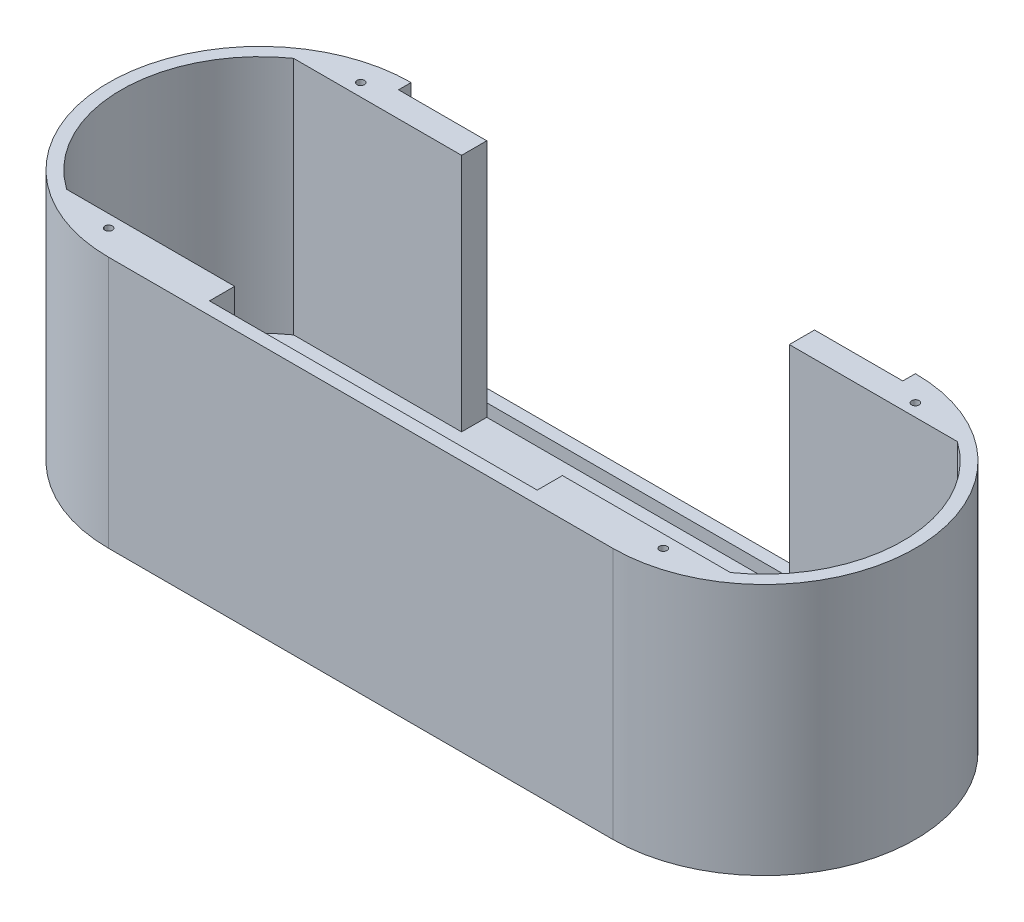
SolidWorks part; units mm, degrees
ref_plane "Front Plane" through (0, 0, 0) normal (0, 0, 1) x (1, 0, 0)
ref_plane "Top Plane" through (0, 0, 0) normal (0, 1, 0) x (1, 0, 0)
ref_plane "Right Plane" through (0, 0, 0) normal (1, 0, 0) x (0, 0, -1)
sketch "Sketch1" plane through (0, 0, 0) normal (0, 1, 0) x (1, 0, 0)
  line L0 (-10, 0) -> (10, 0) construction
  line L1 (-10, 6) -> (10, 6)
  line L2 (-10, -6) -> (10, -6)
  arc A0 (-10, 6) -> (-10, -6) centre (-10, 0) ccw
  arc A1 (10, -6) -> (10, 6) centre (10, 0) ccw
  point P3 (0, 0)
  point P8 (0, 0)
  dimension "D2" = 6
  dimension "D1" = 20
extrude "Boss-Extrude1" add sketch "Sketch1" along normal blind 10
sketch "Sketch2" plane through (0, 10, 0) normal (0, 1, 0) x (1, 0, 0)
  line L0 (-10, 0) -> (10, 0) construction
  line L1 (-10, 5.5) -> (10, 5.5)
  line L2 (-10, -5.5) -> (10, -5.5)
  arc A0 (-10, 5.5) -> (-10, -5.5) centre (-10, 0) ccw
  arc A1 (10, -5.5) -> (10, 5.5) centre (10, 0) ccw
  arc A2 (10, -6) -> (10, 6) centre (10, 0) ccw construction
  point P3 (0, 0)
  point P8 (0, 0)
  point P13 (16, 0)
  point P14 (0, 0)
  dimension "D1" = 5.5
extrude "Cut-Extrude1" cut sketch "Sketch2" against normal blind 9.5
sketch "Sketch3" plane through (0, 0, 0) normal (0, -1, 0) x (1, 0, 0)
  line L0 (-13, 3) -> (-7, -3) construction
  line L1 (-13, -3) -> (-7, 3) construction
  line L2 (0, 6) -> (0, -6) construction
  line L3 (-10, 6) -> (10, 6) construction
  line L4 (10, -6) -> (-10, -6) construction
  line L5 (13, -3) -> (7, 3) construction
  line L6 (13, 3) -> (7, -3) construction
  circle A0 centre (-13, 3) radius 0.15
  circle A1 centre (-7, 3) radius 0.15
  circle A2 centre (-13, -3) radius 0.15
  circle A3 centre (-7, -3) radius 0.15
  circle A4 centre (-12.5, 0) radius 0.5
  circle A5 centre (-12.0225, 1.4695) radius 0.5
  circle A6 centre (-10.7725, 2.3776) radius 0.5
  circle A7 centre (-9.2275, 2.3776) radius 0.5
  circle A8 centre (-7.9775, 1.4695) radius 0.5
  circle A9 centre (-7.5, 0) radius 0.5
  circle A10 centre (-7.9775, -1.4695) radius 0.5
  circle A11 centre (-9.2275, -2.3776) radius 0.5
  circle A12 centre (-10.7725, -2.3776) radius 0.5
  circle A13 centre (-12.0225, -1.4695) radius 0.5
  circle A14 centre (12.0225, -1.4695) radius 0.5
  circle A15 centre (10.7725, -2.3776) radius 0.5
  circle A16 centre (9.2275, -2.3776) radius 0.5
  circle A17 centre (7.9775, -1.4695) radius 0.5
  circle A18 centre (7.5, 0) radius 0.5
  circle A19 centre (7.9775, 1.4695) radius 0.5
  circle A20 centre (9.2275, 2.3776) radius 0.5
  circle A21 centre (10.7725, 2.3776) radius 0.5
  circle A22 centre (12.0225, 1.4695) radius 0.5
  circle A23 centre (12.5, 0) radius 0.5
  circle A24 centre (7, -3) radius 0.15
  circle A25 centre (13, -3) radius 0.15
  circle A26 centre (7, 3) radius 0.15
  circle A27 centre (13, 3) radius 0.15
  point P8 (-10, 0)
  point P33 (-10, 0)
  point P66 (10, 0)
  point P67 (-7.2566, 0)
  point P68 (-7.2332, 0)
  dimension "D1" = 0.3
  dimension "D5" = 1
  dimension "D2" = 6
  dimension "D3" = 6
  dimension "D6" = 2.5
  dimension "D4" = 10
extrude "Cut-Extrude2" cut sketch "Sketch3" against normal through all
sketch "Sketch4" plane through (0, 0, 0) normal (0, -1, 0) x (1, 0, 0)
  line L0 (-4.572, -2.794) -> (4.572, 2.794) construction
  line L1 (-4.35, -2.65) -> (4.35, -2.65)
  line L2 (-4.35, -2.65) -> (-4.35, 2.65)
  line L3 (-4.35, 2.65) -> (4.35, 2.65)
  line L4 (4.35, -2.65) -> (4.35, 2.65)
  line L5 (-4.35, -2.65) -> (4.35, 2.65) construction
  line L6 (-4.35, 2.65) -> (4.35, -2.65) construction
  circle A0 centre (-4.572, 2.794) radius 0.1
  circle A1 centre (4.572, 2.794) radius 0.1
  circle A2 centre (-4.572, -2.794) radius 0.1
  circle A3 centre (4.572, -2.794) radius 0.1
  point P0 (0, 0)
  point P14 (0, 0)
  dimension "D3" = 0.2
  dimension "D1" = 8.7
  dimension "D2" = 5.3
  dimension "D4" = 9.144
  dimension "D5" = 5.588
extrude "Cut-Extrude3" cut sketch "Sketch4" against normal through all
sketch "Sketch5" plane through (0, 0, -6) normal (0, 0, -1) x (-1, 0, 0)
  line L0 (10, 10) -> (10, 0) construction
  line L1 (-10, 10) -> (10, 10)
  line L2 (-10, 10) -> (-10, 1)
  line L3 (-10, 1) -> (10, 1)
  line L4 (10, 10) -> (10, 1)
  line L5 (-10, 0) -> (10, 0) construction
  point P5 (10, 1.8219)
  point P6 (0, 0)
  point P7 (0, 0)
  dimension "D1" = 1
extrude "Cut-Extrude5" cut sketch "Sketch5" against normal up to surface (0.5 mm away) contours L2 L1 L4 L3 up to face at (0, 5.25, -5.5)
sketch "Sketch6" plane through (0, 0.5, 0) normal (0, 1, 0) x (1, 0, 0)
  line L0 (0, 5.5) -> (0, -6) construction
  line L1 (-10, 5.5) -> (-6.5, 5.5)
  line L2 (-10, 5.5) -> (-10, 4.5)
  line L3 (-10, 4.5) -> (-6.5, 4.5)
  line L4 (-6.5, 5.5) -> (-6.5, 4.5)
  line L5 (-10, -5.5) -> (-6.5, -5.5)
  line L6 (-10, -5.5) -> (-10, -4.5)
  line L7 (-10, -4.5) -> (-6.5, -4.5)
  line L8 (-6.5, -5.5) -> (-6.5, -4.5)
  line L9 (10, 5.5) -> (-10, 5.5) construction
  line L10 (-10, -6) -> (10, -6) construction
  line L11 (6.5, -5.5) -> (6.5, -4.5)
  line L12 (10, -4.5) -> (6.5, -4.5)
  line L13 (10, -5.5) -> (10, -4.5)
  line L14 (10, -5.5) -> (6.5, -5.5)
  line L15 (6.5, 5.5) -> (6.5, 4.5)
  line L16 (10, 4.5) -> (6.5, 4.5)
  line L17 (10, 5.5) -> (10, 4.5)
  line L18 (10, 5.5) -> (6.5, 5.5)
  line L19 (-10, 4.5) -> (-13.1623, 4.5)
  line L20 (-10, -4.5) -> (-13.1623, -4.5)
  line L21 (10, 5.5) -> (10, 4.5)
  line L22 (10, 4.5) -> (13.1623, 4.5)
  line L23 (10, -5.5) -> (10, -4.5)
  line L24 (10, -4.5) -> (13.1623, -4.5)
  arc A0 (-10, 5.5) -> (-10, -5.5) centre (-10, 0) ccw construction
  arc A1 (-13.1623, 4.5) -> (-10, 5.5) centre (-10, 0) cw
  arc A2 (-10, -5.5) -> (-13.1623, -4.5) centre (-10, 0) cw
  arc A3 (13.1623, 4.5) -> (10, 5.5) centre (10, 0) ccw
  arc A4 (10, -5.5) -> (13.1623, -4.5) centre (10, 0) ccw
  arc A5 (10, -5.5) -> (10, 5.5) centre (10, 0) ccw construction
  point P32 (0, 0)
  point P36 (0, 0)
  point P40 (0, 0)
  arc M44 (-10, 5.5) -> (-10, -5.5) centre (-10, 0) ccw
  line M45 (-10, -5.5) -> (10, -5.5)
  arc M46 (10, -5.5) -> (10, 5.5) centre (10, 0) ccw
  line M47 (10, 5.5) -> (-10, 5.5)
  dimension "D1" = 1
  dimension "D2" = 1
  dimension "D3" = 3.5
extrude "Boss-Extrude5" add sketch "Sketch6" along normal blind 9.5 contours L13 L12 L11 M45 | L17 L15 L16 M47 | L17 L22 M46 | L24 L13 M46 | L8 L7 L6 M45 | L4 L2 L3 M47 | L19 L2 M44 | L6 L20 M44
scale "Scale2" scale about centroid uniform scaling yes scale factor 10
sketch "Sketch9" plane through (0, 63.4226, 0) normal (0, 1, 0) x (1, 0, 0)
  line L0 (-110, 57.3742) -> (110, 57.3742) construction
  line L3 (131.6228, -37.6258) -> (65, -37.6258) construction
  circle A0 centre (-110, 57.3742) radius 1.5
  circle A1 centre (-110, -42.6258) radius 1.5
  circle A2 centre (110, -42.6258) radius 1.5
  circle A3 centre (110, 57.3742) radius 1.5
  point P8 (0, 57.3742)
  dimension "D1" = 3
  dimension "D2" = 220
  dimension "D3" = 100
  dimension "D5" = 5
extrude "Cut-Extrude6" cut sketch "Sketch9" against normal blind 10
